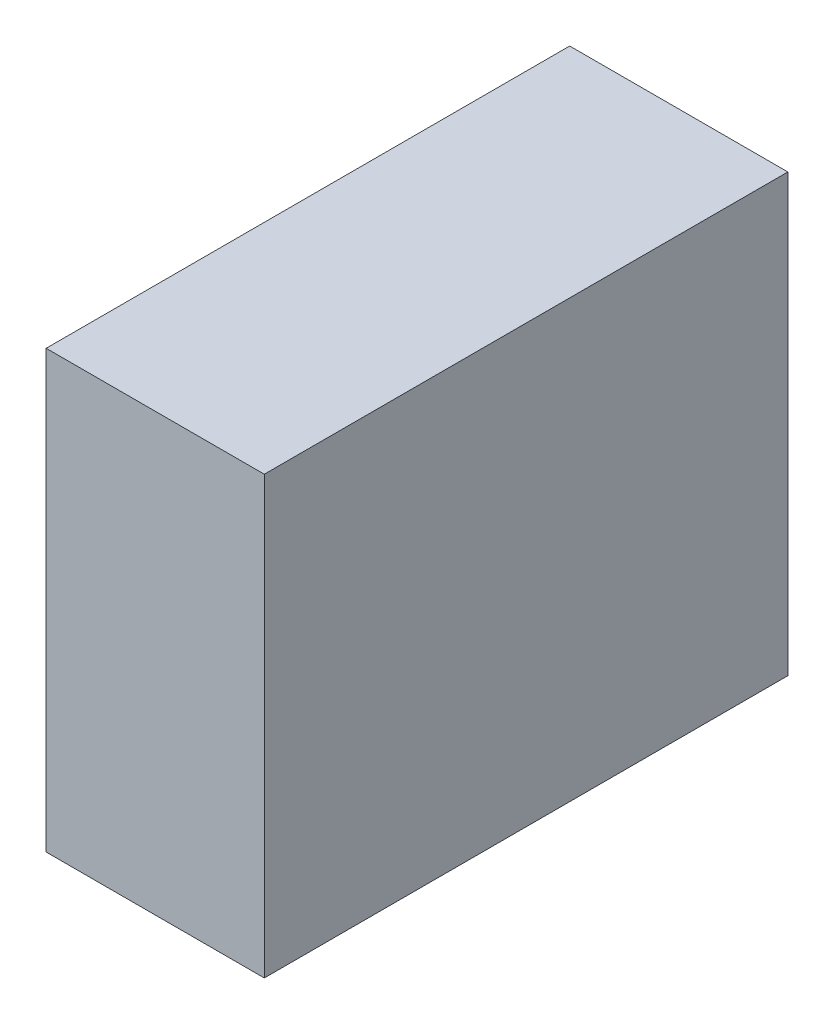
SolidWorks part; units mm, degrees
ref_plane "Front Plane" through (0, 0, 0) normal (0, 0, 1) x (1, 0, 0)
ref_plane "Top Plane" through (0, 0, 0) normal (0, 1, 0) x (1, 0, 0)
ref_plane "Right Plane" through (0, 0, 0) normal (1, 0, 0) x (0, 0, -1)
other "Configuration Table"
sketch "Sketch1" plane through (0, 0, 0) normal (0, 0, 1) x (1, 0, 0)
  line L1 (320, 180) -> (370, 180)
  line L2 (320, 180) -> (320, 280)
  line L3 (320, 280) -> (370, 280)
  line L4 (370, 180) -> (370, 280)
extrude "PACK_pano_step_surucu_1" add sketch "Sketch1" against normal blind 120 from offset 128 separate body
